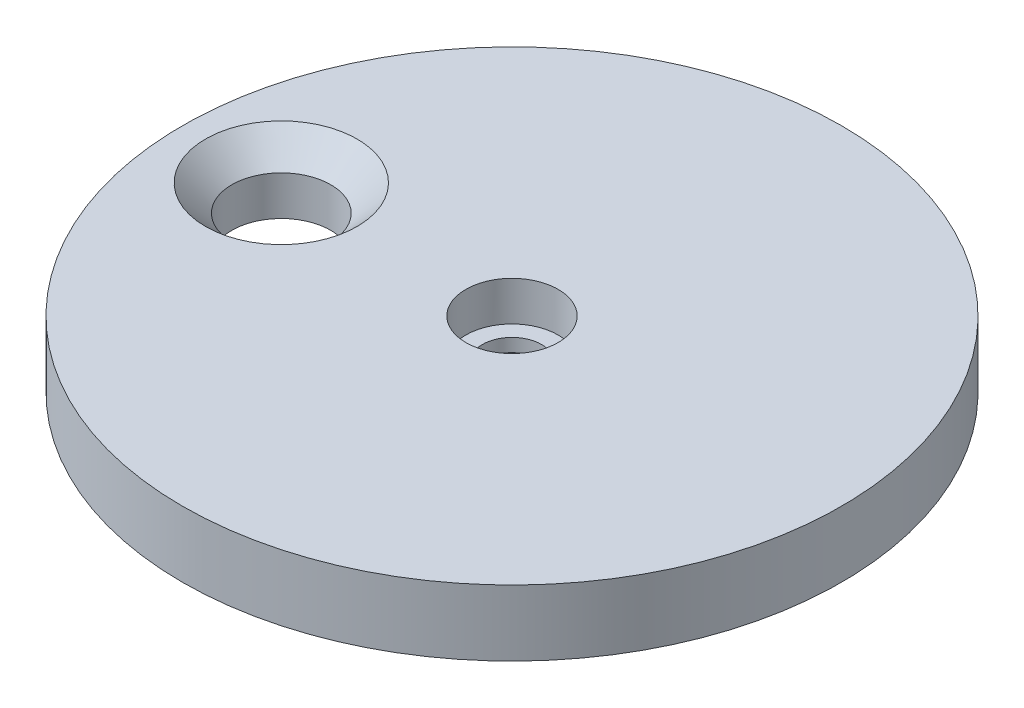
SolidWorks part; units mm, degrees
ref_plane "Front" through (0, 0, 0) normal (0, 0, 1) x (1, 0, 0)
ref_plane "Top" through (0, 0, 0) normal (0, 1, 0) x (1, 0, 0)
ref_plane "Right" through (0, 0, 0) normal (1, 0, 0) x (0, 0, -1)
sketch "Sketch1" plane through (0, 0, 0) normal (0, 1, 0) x (1, 0, 0)
  circle A0 centre (0, 0) radius 50
  circle A1 centre (-35, 0) radius 7.5
  dimension "D1" = 100
  dimension "D2" = 15
  dimension "D3" = 35
extrude "Boss-Extrude1" add sketch "Sketch1" along normal blind 10
sketch "Sketch6" plane through (0, 0, 0) normal (0, 0, 1) x (1, 0, 0)
  line L0 (0, 0) -> (0, 50) construction
  dimension "D1" = 50
chamfer "Chamfer1" distance 4 angle 45 1 edges at (-35, 10, 7.5)
sketch "Sketch2" plane through (0, 0, 0) normal (0, -1, 0) x (1, 0, 0)
  line L0 (-17, -2.5) -> (-4.43, -4.43)
  line L1 (0, 0) -> (-17, 0) construction
  line L2 (-17, 2.5) -> (-4.43, 4.43)
  line L3 (0, 0) -> (0, 50) construction
  line L4 (-2.5, 17) -> (-4.43, 4.43)
  line L5 (2.5, 17) -> (4.43, 4.43)
  line L6 (17, 2.5) -> (4.43, 4.43)
  line L7 (17, -2.5) -> (4.43, -4.43)
  line L8 (2.5, -17) -> (4.43, -4.43)
  line L9 (-2.5, -17) -> (-4.43, -4.43)
  arc A0 (-17, 2.5) -> (-17, -2.5) centre (-17, 0) ccw
  circle A1 centre (0, 0) radius 50 construction
  arc A2 (2.5, 17) -> (-2.5, 17) centre (0, 17) ccw
  arc A3 (17, -2.5) -> (17, 2.5) centre (17, 0) ccw
  arc A4 (-2.5, -17) -> (2.5, -17) centre (0, -17) ccw
  point P28 (0, 0)
  dimension "D2" = 5
  dimension "D1" = 17
  dimension "D3" = 4.43
  dimension "D4" = 4
extrude "Cut-Extrude1" cut sketch "Sketch2" against normal blind 2
sketch "Sketch3" plane through (0, 2, 0) normal (0, -1, 0) x (1, 0, 0)
  circle A0 centre (0, 0) radius 4.5
  dimension "D1" = 9
extrude "Cut-Extrude2" cut sketch "Sketch3" against normal up to next
sketch "Sketch4" plane through (0, 2, 0) normal (0, -1, 0) x (1, 0, 0)
  circle A0 centre (-16, 0) radius 1
  circle A1 centre (0, 16) radius 1
  circle A2 centre (16, 0) radius 1
  circle A3 centre (0, -16) radius 1
  point P13 (0, 0)
  dimension "D2" = 2
  dimension "D1" = 16
  dimension "D3" = 4
extrude "Cut-Extrude3" cut sketch "Sketch4" against normal offset from surface (7 mm away) 1 up to face at (0, 10, 4.5)
sketch "Sketch7" plane through (0, 10, 0) normal (0, 1, 0) x (1, 0, 0)
  circle A0 centre (0, 0) radius 7
  dimension "D1" = 14
extrude "Cut-Extrude4" cut sketch "Sketch7" against normal offset from surface (6 mm away) 2 up to face at (-16, 2, -1)
